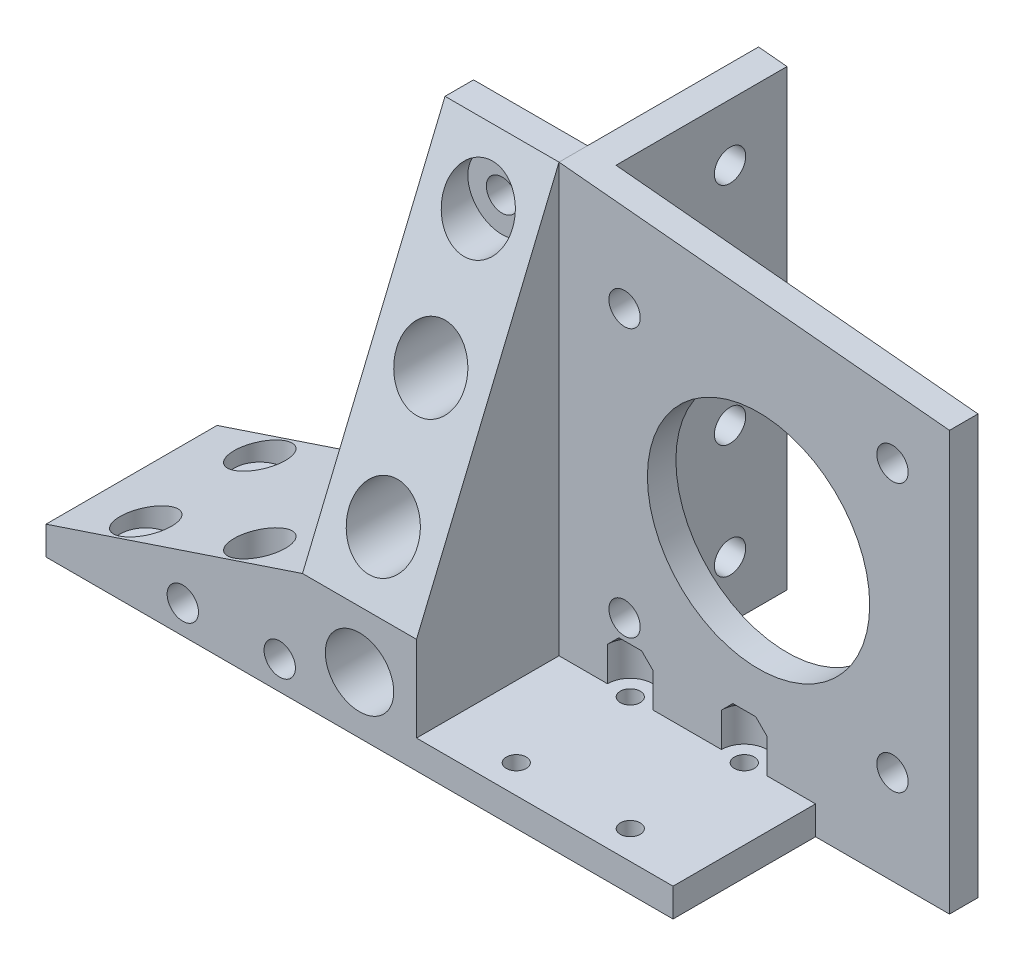
SolidWorks part; units mm, degrees
ref_plane "Plan de face" through (0, 0, 0) normal (0, 0, 1) x (1, 0, 0)
ref_plane "Plan de dessus" through (0, 0, 0) normal (0, 1, 0) x (1, 0, 0)
ref_plane "Plan de droite" through (0, 0, 0) normal (1, 0, 0) x (0, 0, -1)
sketch "Esquisse1" plane through (0, 0, 0) normal (0, 0, 1) x (1, 0, 0)
  line L1 (-9.5845, 32.7642) -> (10.4155, 32.7642)
  line L2 (-9.5845, 32.7642) -> (-9.5845, -47.2358)
  line L3 (-9.5845, -47.2358) -> (10.4155, -47.2358)
  line L4 (10.4155, 32.7642) -> (10.4155, -47.2358)
  circle A0 centre (0.4155, 22.7642) radius 2.75
  circle A1 centre (0.4155, -17.2358) radius 2.75
  circle A2 centre (0.4155, 2.7642) radius 2.75
  circle A3 centre (0.4155, -37.2358) radius 2.75
  point P13 (0.4155, -47.2358)
  dimension "D3" = 5.5
  dimension "D1" = 20
  dimension "D2" = 80
  dimension "D4" = 10
  dimension "D5" = 20
  dimension "D6" = 10
  dimension "D7" = 20
extrude "Boss.-Extru.1" add sketch "Esquisse1" along normal blind 5
sketch "Esquisse3" plane through (0, 0, 5) normal (0, 0, 1) x (1, 0, 0)
  line L0 (-9.5845, -47.2358) -> (-54.5845, -47.2358)
  line L1 (-54.5845, -47.2358) -> (-54.5845, -42.2358)
  line L2 (-54.5845, -42.2358) -> (-9.5845, -27.2358)
  line L3 (-9.5845, 32.7642) -> (-9.5845, -47.2358) construction
  line L4 (-9.5845, -27.2358) -> (-9.5845, -47.2358)
  line L5 (10.4155, -47.2358) -> (55.4155, -47.2358)
  line L6 (55.4155, -47.2358) -> (55.4155, -42.2358)
  line L7 (55.4155, -42.2358) -> (10.4155, -42.2358)
  line L8 (10.4155, -47.2358) -> (10.4155, 32.7642) construction
  line L9 (10.4155, -42.2358) -> (10.4155, -47.2358)
  dimension "D1" = 5
  dimension "D2" = 45
  dimension "D3" = 20
extrude "Boss.-Extru.2" add sketch "Esquisse3" against normal blind 5
sketch "Esquisse4" plane through (0, 0, 5) normal (0, 0, 1) x (1, 0, 0)
  line L0 (55.4155, -47.2358) -> (55.4155, -42.2358) construction
  line L1 (55.4155, -42.2358) -> (10.4155, -42.2358) construction
  line L2 (-9.5845, -27.2358) -> (-54.5845, -42.2358) construction
  line L3 (-54.5845, -42.2358) -> (-54.5845, -47.2358) construction
  line L4 (-54.5845, -47.2358) -> (55.4155, -47.2358) construction
  line L5 (55.4155, -47.2358) -> (55.4155, -42.2358)
  line L6 (55.4155, -42.2358) -> (10.4155, -42.2358)
  line L7 (-9.5845, -27.2358) -> (-54.5845, -42.2358)
  line L8 (-54.5845, -42.2358) -> (-54.5845, -47.2358)
  line L9 (-54.5845, -47.2358) -> (55.4155, -47.2358)
  line L11 (-9.5845, -27.2358) -> (10.4155, -27.2358)
  line L12 (10.4155, -42.2358) -> (10.4155, 32.7642) construction
  line L13 (10.4155, -27.2358) -> (10.4155, -42.2358)
  circle A0 centre (0.4155, -37.2358) radius 2.75 construction
  circle A1 centre (0.4155, -37.2358) radius 2.75
extrude "Boss.-Extru.3" add sketch "Esquisse4" along normal blind 25
sketch "Esquisse5" plane through (-9.5845, 0, 0) normal (-1, 0, 0) x (0, 0, 1)
  line L0 (5, -27.2358) -> (30, -27.2358)
  line L1 (30, -27.2358) -> (5, 32.7642)
  line L2 (5, 32.7642) -> (5, -27.2358)
extrude "Boss.-Extru.4" add sketch "Esquisse5" against normal up to surface (20 mm away) up to face at (10.4155, -12.2358, 11.6667)
sketch "Esquisse6" plane through (0, 0, 5) normal (0, 0, -1) x (-1, 0, 0)
  circle A0 centre (-0.4155, 2.7642) radius 6
  circle A1 centre (-0.4155, -17.2358) radius 6
  circle A2 centre (-0.4155, 22.7642) radius 6
  circle A3 centre (-0.4155, -37.2358) radius 6
  dimension "D1" = 12
extrude "Enlèv. mat.-Extru.1" cut sketch "Esquisse6" against normal up to next
sketch "Esquisse7" plane through (0, -47.2358, 0) normal (0, -1, 0) x (1, 0, 0)
  line L0 (-42.0845, 25) -> (-22.0845, 25) construction
  line L1 (-22.0845, 25) -> (-22.0845, 5) construction
  line L2 (-54.5845, 0) -> (-54.5845, 30) construction
  line L3 (22.9155, 5) -> (22.9155, 25) construction
  line L4 (22.9155, 25) -> (42.9155, 25) construction
  line L5 (55.4155, 0) -> (55.4155, 30) construction
  circle A0 centre (-42.0845, 25) radius 1.75
  circle A1 centre (-22.0845, 25) radius 1.75
  circle A2 centre (-22.0845, 5) radius 1.75
  circle A3 centre (-42.0845, 5) radius 1.75
  circle A4 centre (42.9155, 25) radius 1.75
  circle A5 centre (42.9155, 5) radius 1.75
  circle A6 centre (22.9155, 5) radius 1.75
  circle A7 centre (22.9155, 25) radius 1.75
  point P8 (-22.0845, 15)
  point P11 (-54.5845, 15)
  point P12 (-32.0845, 25)
  point P21 (22.9155, 15)
  point P24 (55.4155, 15)
  point P25 (32.9155, 25)
  dimension "D1" = 3.5
  dimension "D4" = 3.5
  dimension "D2" = 20
  dimension "D3" = 22.5
  dimension "D5" = 20
  dimension "D6" = 22.5
extrude "Enlèv. mat.-Extru.2" cut sketch "Esquisse7" against normal up to next
ref_plane "Plan3" through (0, -42.2358, 0) normal (0, -1, 0) x (-1, 0, 0)
sketch "Esquisse9" plane through (0, -42.2358, 0) normal (0, -1, 0) x (-1, 0, 0)
  circle A0 centre (42.0845, -25) radius 4.5
  circle A1 centre (22.0845, -25) radius 4.5
  circle A2 centre (22.0845, -5) radius 4.5
  circle A3 centre (42.0845, -5) radius 4.5
  dimension "D1" = 9
extrude "Enlèv. mat.-Extru.3" cut sketch "Esquisse9" against normal up to next
sketch "Esquisse11" plane through (0, 0, 0) normal (0, 0, -1) x (-1, 0, 0)
  line L0 (-10.4155, -42.2358) -> (-55.4155, -42.2358)
  line L2 (-10.4155, -42.2358) -> (-10.4155, 32.7642)
  line L3 (-10.4155, -42.2358) -> (-10.4155, 32.7642) construction
  line L4 (-10.4155, 32.7642) -> (-78.9155, 26.2642)
  line L5 (-55.4155, -42.2358) -> (-55.4155, -47.2358)
  line L6 (-55.4155, -47.2358) -> (-78.9155, -47.2358)
  line L7 (-78.9155, -47.2358) -> (-78.9155, 26.2642)
  line L8 (-68.9155, 16.2642) -> (-68.9155, -30.7358) construction
  line L9 (-68.9155, -30.7358) -> (-21.9155, -30.7358) construction
  circle A0 centre (-45.4155, -7.2358) radius 19.5
  circle A1 centre (-21.9155, 16.2642) radius 2.75
  circle A2 centre (-21.9155, -30.7358) radius 2.75
  circle A3 centre (-68.9155, -30.7358) radius 2.75
  circle A4 centre (-68.9155, 16.2642) radius 2.75
  point P22 (-45.4155, -30.7358)
  point P23 (-68.9155, -7.2358)
  dimension "D3" = 39
  dimension "D4" = 5.5
  dimension "D1" = 35
  dimension "D2" = 35
  dimension "D5" = 47
  dimension "D6" = 10
  dimension "D7" = 10
extrude "Boss.-Extru.5" add sketch "Esquisse11" against normal blind 5
sketch "Esquisse12" plane through (0, -42.2358, 0) normal (0, 1, 0) x (1, 0, 0)
  circle A0 centre (22.9155, -5) radius 4
  circle A1 centre (42.9155, -5) radius 4
  arc A2 (21.1655, -5) -> (24.6655, -5) centre (22.9155, -5) ccw construction
  arc A3 (41.1655, -5) -> (44.6655, -5) centre (42.9155, -5) ccw construction
  dimension "D1" = 8
extrude "Enlèv. mat.-Extru.5" cut sketch "Esquisse12" along normal blind 8
chamfer "Chanfrein1" distance 2 angle 45 2 edges at (42.9155, -34.2358, 1) (22.9155, -34.2358, 1)
sketch "Esquisse13" plane through (0, 0, 0) normal (0, 0, -1) x (-1, 0, 0)
  line L0 (54.5845, -47.2358) -> (-78.9155, -47.2358) construction
  line L1 (-10.4155, 32.7642) -> (-15.4155, 32.2898)
  line L2 (-10.4155, 32.7642) -> (-10.4155, -47.2358)
  line L3 (-10.4155, -47.2358) -> (-15.4155, -47.2358)
  line L4 (-15.4155, 32.2898) -> (-15.4155, -47.2358)
  line L5 (-10.4155, 32.7642) -> (-78.9155, 26.2642) construction
  dimension "D1" = 5
extrude "Boss.-Extru.6" add sketch "Esquisse13" along normal blind 30
sketch "Esquisse14" plane through (15.4155, 0, 0) normal (1, 0, 0) x (0, 0, -1)
  line L0 (30, 32.2898) -> (30, -47.2358) construction
  line L1 (30, 32.2898) -> (0, 32.2898) construction
  line L2 (30, -47.2358) -> (0, -47.2358) construction
  circle A0 centre (20, 22.2898) radius 2.75
  circle A1 centre (20, 2.2898) radius 2.75
  circle A2 centre (20, -17.2358) radius 2.75
  circle A3 centre (20, -37.2358) radius 2.75
  dimension "D3" = 5.5
  dimension "D1" = 10
  dimension "D2" = 10
  dimension "D4" = 10
  dimension "D5" = 20
  dimension "D6" = 20
extrude "Enlèv. mat.-Extru.6" cut sketch "Esquisse14" against normal up to next
sketch "Esquisse15" plane through (0, 0, 30) normal (0, 0, 1) x (1, 0, 0)
  line L0 (-54.5845, -47.2358) -> (55.4155, -47.2358) construction
  line L1 (-30.5845, -42.2358) -> (-13.5845, -42.2358) construction
  line L2 (-20.3345, -42.2358) -> (-23.8345, -42.2358) construction
  line L3 (-20.3345, -42.2358) -> (-23.8345, -42.2358) construction
  circle A0 centre (-13.5845, -42.2358) radius 2.75
  circle A1 centre (-30.5845, -42.2358) radius 2.75
  point P12 (-22.0845, -42.2358)
  point P13 (-22.0845, -42.2358)
  dimension "D1" = 5.5
  dimension "D3" = 17
  dimension "D4" = 5
extrude "Enlèv. mat.-Extru.7" cut sketch "Esquisse15" against normal up to next
